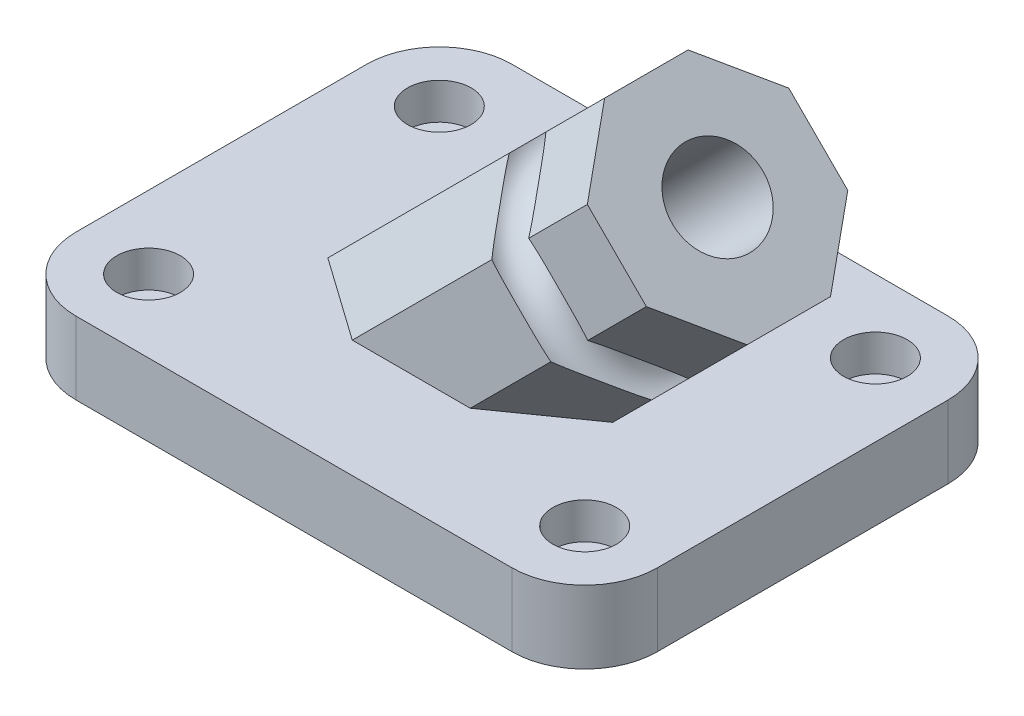
SolidWorks part; units mm, degrees
material "2024-O"
ref_plane "Front Plane" through (0, 0, 0) normal (0, 0, 1) x (1, 0, 0)
ref_plane "Top Plane" through (0, 0, 0) normal (0, 1, 0) x (1, 0, 0)
ref_plane "Right Plane" through (0, 0, 0) normal (1, 0, 0) x (0, 0, -1)
sketch "Bottom Sketch" plane through (0, 0, 0) normal (0, 1, 0) x (1, 0, 0)
  line L1 (50.8, -38.1) -> (-50.8, -38.1)
  line L2 (50.8, -38.1) -> (50.8, 38.1)
  line L3 (50.8, 38.1) -> (-50.8, 38.1)
  line L4 (-50.8, -38.1) -> (-50.8, 38.1)
  line L5 (50.8, -38.1) -> (-50.8, 38.1) construction
  line L6 (50.8, 38.1) -> (-50.8, -38.1) construction
  point P0 (0, 0)
  dimension "D1" = 101.6
  dimension "D2" = 76.2
extrude "Base Extrude" add sketch "Bottom Sketch" along normal blind 12.7
fillet "Corner Fillets" radius 12.7 4 edges at (-50.8, 6.35, -38.1) (50.8, 6.35, -38.1) (50.8, 6.35, 38.1) (-50.8, 6.35, 38.1)
sketch "Top Circular Sketch" plane through (0, 12.7, 0) normal (0, 1, 0) x (1, 0, 0)
  circle A0 centre (-38.1, -25.4) radius 5.5626
  dimension "D1" = 11.1252
extrude "Top Circular Cut" cut sketch "Top Circular Sketch" against normal blind 6.35
sketch "Bottom Circular Sketch" plane through (0, 6.35, 0) normal (0, 1, 0) x (1, 0, 0)
  circle A0 centre (-38.1, -25.4) radius 3.3782
  dimension "D1" = 6.7564
extrude "Bottom Circular Cut" cut sketch "Bottom Circular Sketch" against normal through all
mirror "Vertical Mirror" about plane through (0, 0, 0) normal (0, 0, 1) of "Bottom Circular Cut", "Top Circular Cut"
mirror "Horizontal Mirror" about plane through (0, 0, 0) normal (1, 0, 0) of "Vertical Mirror", "Top Circular Cut", "Bottom Circular Cut"
sketch "Base Sketch" plane through (0, 12.7, 0) normal (0, 1, 0) x (1, 0, 0)
  line L0 (0, 38.1) -> (0, -38.1) construction
  line L1 (38.1, 38.1) -> (-38.1, 38.1) construction
  line L2 (-38.1, -38.1) -> (38.1, -38.1) construction
  line L3 (-50.8, 0) -> (50.8, 0) construction
  line L4 (-50.8, 25.4) -> (-50.8, -25.4) construction
  line L5 (50.8, -25.4) -> (50.8, 25.4) construction
sketch "Angular Sketch" plane through (0, 0, 0) normal (0, 0, 1) x (1, 0, 0)
  line L0 (0, 12.7) -> (35.921, 48.621) construction
  line L1 (-50.8, 12.7) -> (50.8, 12.7) construction
  point P5 (0, 0)
  dimension "D1" = 45
  dimension "D2" = 50.8
ref_plane "Octagonal Plane" through (35.921, 48.621, 0) normal (0.7071, 0.7071, 0) x (0.7071, -0.7071, 0)
sketch "Octagonal Sketch" plane through (35.921, 48.621, 0) normal (0.7071, 0.7071, 0) x (0.7071, -0.7071, 0)
  line L0 (-7.2901, 17.5999) -> (-17.5999, 7.2901)
  line L1 (-17.5999, -7.2901) -> (-7.2901, -17.5999)
  line L2 (-7.2901, -17.5999) -> (7.2901, -17.5999)
  line L3 (7.2901, -17.5999) -> (17.5999, -7.2901)
  line L4 (17.5999, -7.2901) -> (17.5999, 7.2901)
  line L5 (17.5999, 7.2901) -> (7.2901, 17.5999)
  line L6 (7.2901, 17.5999) -> (-7.2901, 17.5999)
  line L7 (-17.5999, 7.2901) -> (-17.5999, -7.2901)
  line L8 (-35.921, 25.4) -> (-35.921, -25.4) construction
  circle A0 centre (0, 0) radius 19.05 construction
  point P13 (-5.154, 12.4428)
  dimension "D1" = 38.1
extrude "Octagonal Extrude" add sketch "Octagonal Sketch" against normal up to next
sketch "Center Sketch" plane through (42.271, 42.271, 0) normal (0.7071, 0.7071, 0) x (0, 0, -1)
  circle A0 centre (0, 8.9803) radius 7.9375
  dimension "D1" = 15.875
extrude "Center Cut" cut sketch "Center Sketch" against normal through all contours A0
sketch "Midline Sketch" plane through (0, 0, 0) normal (0, 0, 1) x (1, 0, 0)
  line L0 (0, 12.7) -> (22.4506, 35.1506) construction
  line L1 (0, 12.7) -> (35.921, 48.621) construction
  point P5 (0, 0)
sketch "Wall Sketch" plane through (0, 0, 17.5999) normal (0, 0, 1) x (1, 0, 0)
  line L0 (-10.3098, 12.7) -> (0, 12.7) construction
  line L1 (10.3098, 12.7) -> (-10.3098, 12.7) construction
sketch "Parallel Sketch" plane through (0, 0, 17.5999) normal (0, 0, 1) x (1, 0, 0)
  line L0 (0, 12.7) -> (22.4506, 35.1506) construction
  line L1 (10.3098, 12.7) -> (-10.3098, 12.7) construction
  dimension "D1" = 31.75
  dimension "D2" = 45
ref_plane "Centered Plane" through (-6.35, 6.35, 0) normal (-0.7071, 0.7071, 0) x (0, 0, 1)
sketch "Radius Sketch" plane through (-6.35, 6.35, 0) normal (-0.7071, 0.7071, 0) x (0, 0, 1)
  circle A0 centre (17.5999, 40.7303) radius 4.7752
  dimension "D1" = 9.5504
revolve "Radial Cut" cut sketch "Radius Sketch" angle 360 about L0
